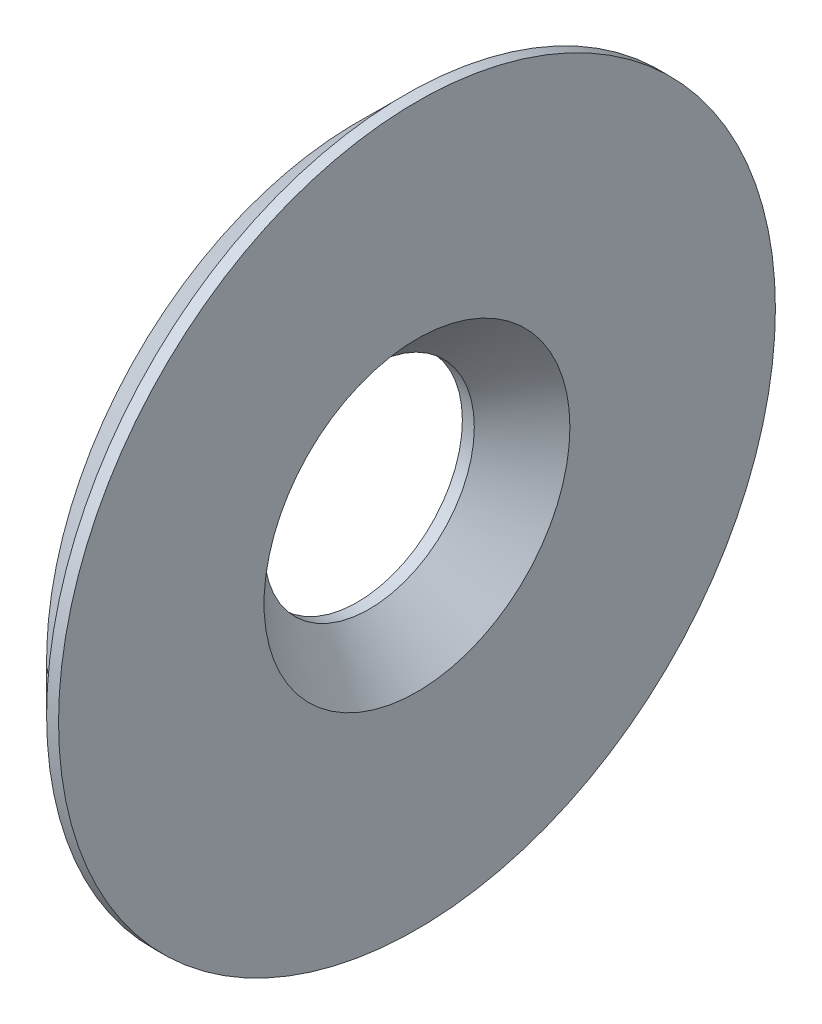
SolidWorks part; units mm, degrees
material "Plain Carbon Steel"
ref_plane "Plane1" through (0, 0, 0) normal (0, 0, 1) x (1, 0, 0)
ref_plane "Plane2" through (0, 0, 0) normal (0, 1, 0) x (1, 0, 0)
ref_plane "Plane3" through (0, 0, 0) normal (1, 0, 0) x (0, 0, -1)
sketch "Sketch1" plane through (0, 0, 0) normal (1, 0, 0) x (0, 0, -1)
  circle A0 centre (0, 0) radius 4.4
  circle A1 centre (0, 0) radius 15
  dimension "Insid_dia" = 8.8
  dimension "OutsideDia" = 30
extrude "Base-Extrude" add sketch "Sketch1" along normal blind 2.5
chamfer "Chamfer1" distance 2 angle 45 2 edges at (2.5, 0, -4.4) (0, 0, -15)
